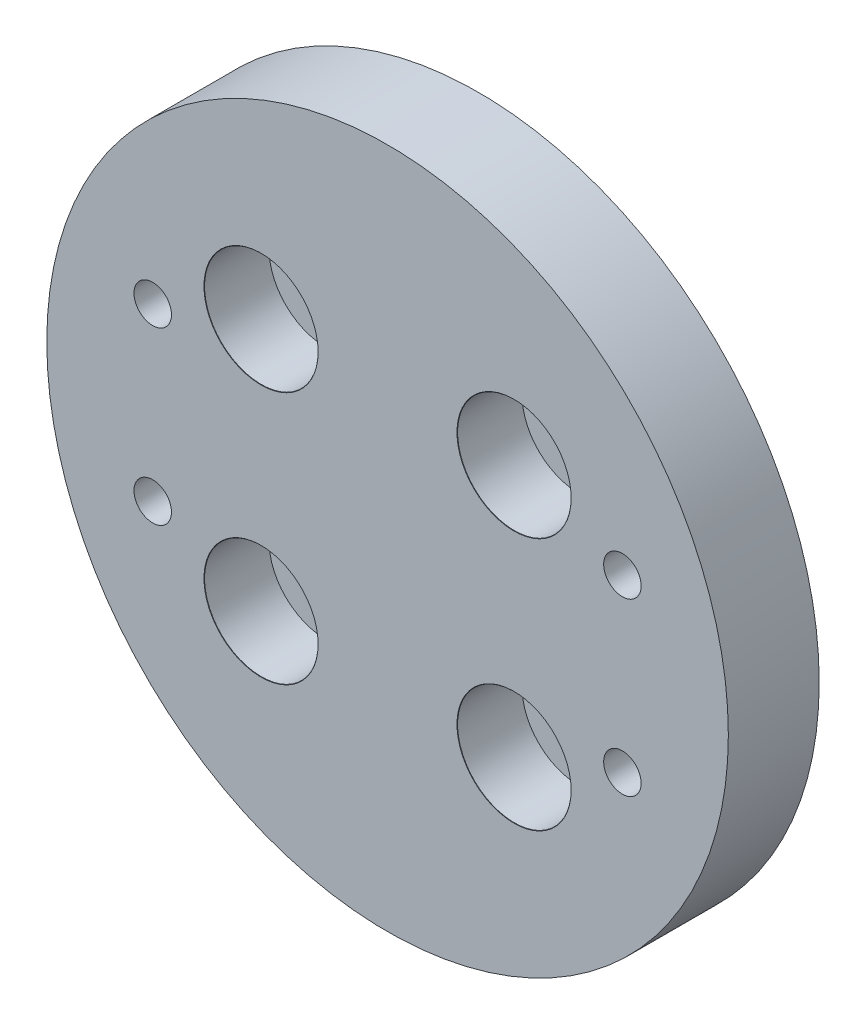
SolidWorks part; units mm, degrees
ref_plane "前视基准面" through (0, 0, 0) normal (0, 0, 1) x (1, 0, 0)
ref_plane "上视基准面" through (0, 0, 0) normal (0, 1, 0) x (1, 0, 0)
ref_plane "右视基准面" through (0, 0, 0) normal (1, 0, 0) x (0, 0, -1)
sketch "草图1" plane through (0, 0, 0) normal (0, 0, 1) x (1, 0, 0)
  circle A1 centre (0, 0) radius 30
  dimension "D1" = 60
extrude "凸台-拉伸1" add sketch "草图1" along normal blind 8
sketch "草图2" plane through (0, 0, 8) normal (0, 0, 1) x (1, 0, 0)
  line L0 (0, 15.75) -> (0, -15.75) construction
  line L1 (0, 0) -> (11.1369, -11.1369) construction
  circle A0 centre (0, 0) radius 15.75 construction
  dimension "D1" = 31.5
  dimension "D2" = 45
hole_wizard "打孔尺寸(%根据)内六角圆柱头螺钉的类型1" positions "草图6" profile "草图7" counterbore size "M5" standard "GB" end condition through all
sketch "草图6" plane through (0, 0, 8) normal (0, 0, 1) x (1, 0, 0)
  point P0 (11.1369, -11.1369)
sketch "草图7" plane through (11.1369, -11.1369, 8) normal (1, 0, 0) x (0, -1, 0)
  line L0 (0, 0) -> (0, 8)
  line L1 (0, 8) -> (2.75, 8)
  line L3 (2.75, 8) -> (2.75, 5.7)
  line L4 (5, 5.7) -> (2.75, 5.7)
  line L5 (5, 5.7) -> (5, 0.025)
  line L6 (5, 0.025) -> (5.025, 0)
  line L7 (5.025, 0) -> (0, 0)
  line L8 (-5, 0.025) -> (-5.025, 0) construction
  line L11 (0, -6.35) -> (0, 107.95) construction
  dimension "通孔孔直径" = 5.5
  dimension "通孔孔深度" = 8
  dimension "柱形沉头孔直径" = 10
  dimension "柱形沉头孔深度" = 5.7
  dimension "近端锥形沉头孔直径" = 10.05
  dimension "近端锥形沉头孔角度" = 90
pattern_circular "阵列(圆周)1" count 4 over 360 about axis through (0, 0, 0) along (0, 0, 1) of "打孔尺寸(%根据)内六角圆柱头螺钉的类型1"
sketch "草图8" plane through (0, 0, 0) normal (0, 0, -1) x (-1, 0, 0)
  line L0 (12, 0) -> (-12, 0) construction
  line L1 (0, 17) -> (0, -17) construction
  point P6 (0, 0)
  dimension "D1" = 12
  dimension "D2" = 17
hole_wizard "M4 螺纹孔1" positions "草图11" profile "草图12" tap size "M4" standard "GB" end condition through all
sketch "草图11" plane through (0, 0, 8) normal (0, 0, 1) x (1, 0, 0)
  point P0 (20.6732, 7.5244)
  point P3 (20.6732, -7.5244)
  point P6 (-20.6732, 7.5244)
  point P9 (-20.6732, -7.5244)
sketch "草图12" plane through (20.6732, 7.5244, 8) normal (1, 0, 0) x (0, -1, 0)
  line L0 (0, 0) -> (0, 8)
  line L1 (0, 8) -> (1.65, 8)
  line L2 (1.65, 8) -> (1.65, 0)
  line L5 (1.65, 0) -> (0, 0)
  line L11 (0, -6.35) -> (0, 107.95) construction
  dimension "通孔螺纹孔钻头直径" = 3.3
  dimension "通孔螺纹孔钻头深度" = 8
cosmetic thread "孔螺蚊线3" parameters "D2"=4
cosmetic thread "孔螺蚊线4" parameters "D2"=4
cosmetic thread "孔螺蚊线5" parameters "D2"=4
cosmetic thread "孔螺蚊线6" parameters "D2"=4
